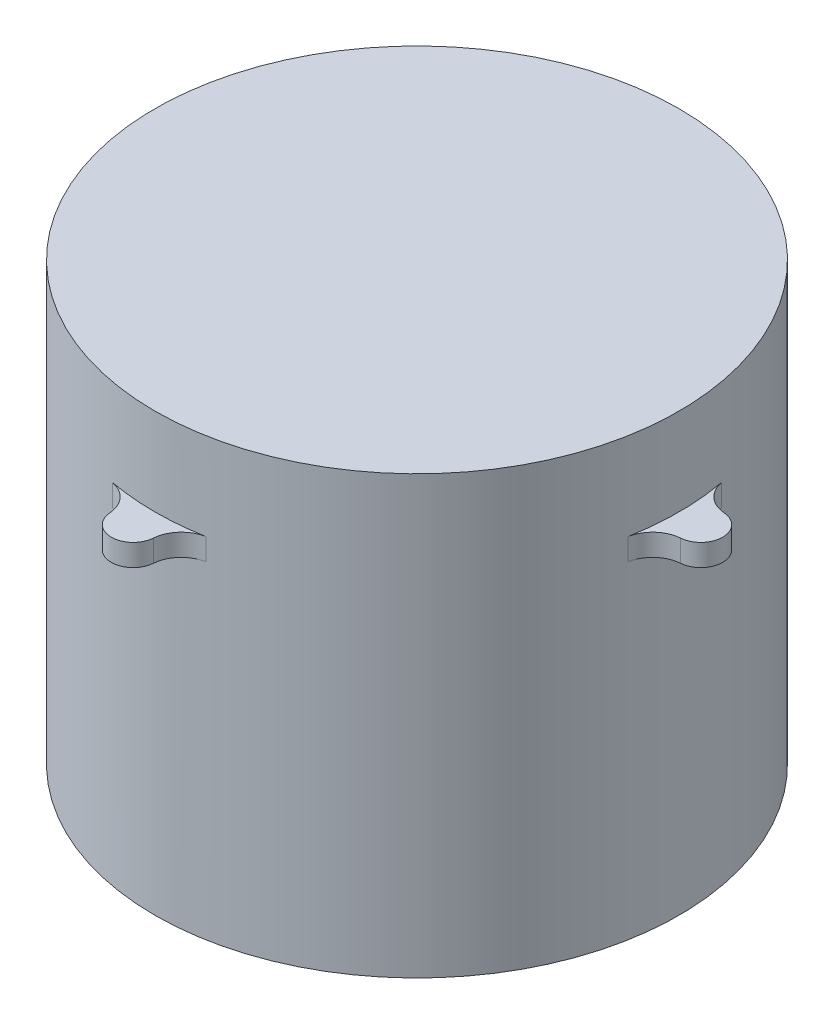
SolidWorks part; units mm, degrees
ref_plane "Front Plane" through (0, 0, 0) normal (0, 0, 1) x (1, 0, 0)
ref_plane "Top Plane" through (0, 0, 0) normal (0, 1, 0) x (1, 0, 0)
ref_plane "Right Plane" through (0, 0, 0) normal (1, 0, 0) x (0, 0, -1)
sketch "Sketch1" plane through (0, 0, 0) normal (0, 1, 0) x (1, 0, 0)
  circle A0 centre (0, 0) radius 60
  dimension "D1" = 120
extrude "Boss-Extrude1" add sketch "Sketch1" along normal blind 100
sketch "Sketch2" plane through (0, 100, 0) normal (0, 1, 0) x (1, 0, 0)
  arc A0 (-10.7144, 59.0356) -> (-59.0356, 10.7144) centre (0, 0) ccw
  arc A1 (4.9852, 65.3846) -> (-4.9852, 65.3846) centre (0, 65) ccw
  arc A2 (-10.7144, 59.0356) -> (-4.9852, 65.3846) centre (-11.9644, 65.9231) ccw
  arc A3 (4.9852, 65.3846) -> (10.7144, 59.0356) centre (11.9644, 65.9231) ccw
  arc A6 (65.3846, -4.9852) -> (65.3846, 4.9852) centre (65, 0) ccw
  arc A7 (65.3846, -4.9852) -> (59.0356, -10.7144) centre (65.9231, -11.9644) ccw
  arc A8 (59.0356, 10.7144) -> (65.3846, 4.9852) centre (65.9231, 11.9644) ccw
  arc A9 (-4.9852, -65.3846) -> (4.9852, -65.3846) centre (0, -65) ccw
  arc A10 (-4.9852, -65.3846) -> (-10.7144, -59.0356) centre (-11.9644, -65.9231) ccw
  arc A11 (10.7144, -59.0356) -> (4.9852, -65.3846) centre (11.9644, -65.9231) ccw
  arc A12 (-65.3846, 4.9852) -> (-65.3846, -4.9852) centre (-65, 0) ccw
  arc A13 (-65.3846, 4.9852) -> (-59.0356, 10.7144) centre (-65.9231, 11.9644) ccw
  arc A14 (-59.0356, -10.7144) -> (-65.3846, -4.9852) centre (-65.9231, -11.9644) ccw
  arc A15 (-59.0356, -10.7144) -> (-10.7144, -59.0356) centre (0, 0) ccw
  arc A16 (59.0356, 10.7144) -> (10.7144, 59.0356) centre (0, 0) ccw
  arc A17 (10.7144, -59.0356) -> (59.0356, -10.7144) centre (0, 0) ccw
  point P33 (0, 0)
  dimension "D1" = 120
  dimension "D2" = 10
  dimension "D4" = 7
  dimension "D3" = 65
  dimension "D5" = 4
extrude "Boss-Extrude2" add sketch "Sketch2" against normal blind 5 from offset 20
